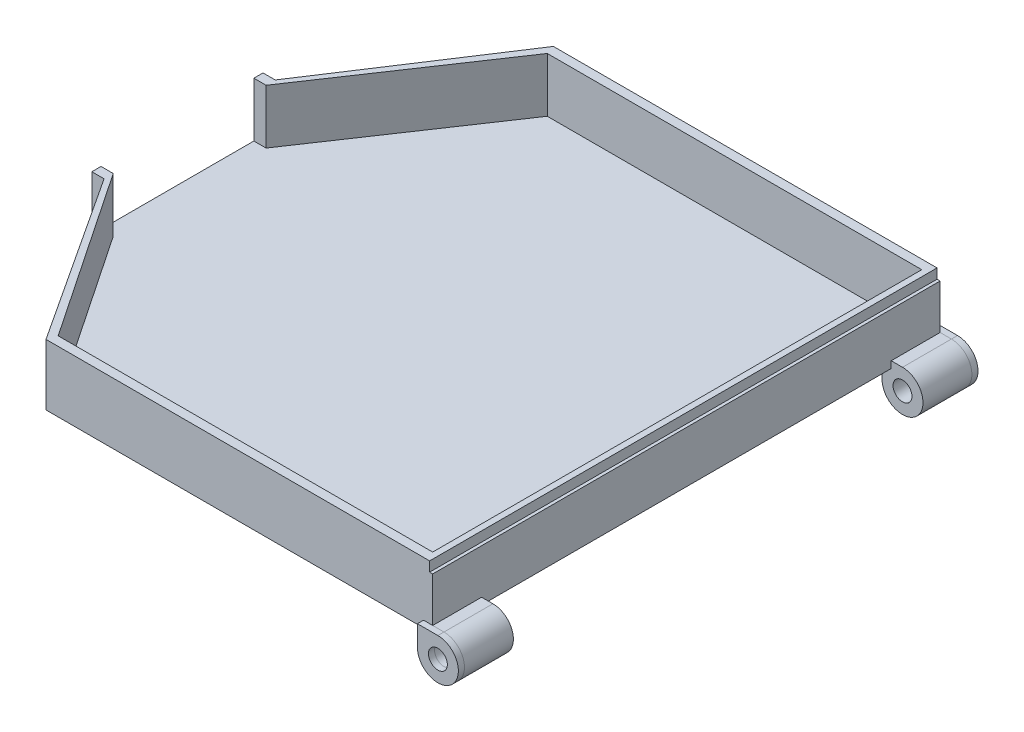
SolidWorks part; units mm, degrees
ref_plane "Спереди" through (0, 0, 0) normal (0, 0, 1) x (1, 0, 0)
ref_plane "Сверху" through (0, 0, 0) normal (0, 1, 0) x (1, 0, 0)
ref_plane "Справа" through (0, 0, 0) normal (1, 0, 0) x (0, 0, -1)
sketch "Эскиз2" plane through (0, 0, 0) normal (0, 0, 1) x (1, 0, 0)
  line L1 (28.097, -1.1018) -> (-25.7907, -1.1018)
  line L2 (28.097, 8.8982) -> (28.097, -0.0018)
  line L3 (28.097, -0.0018) -> (-29.6554, -0.0018)
  line L4 (29.597, 7.2982) -> (29.597, -0.0018)
  line L5 (-25.7907, -1.1018) -> (-31.6554, -1.1018)
  line L6 (29.597, -1.1018) -> (28.097, -1.1018)
  line L7 (28.097, -1.1018) -> (28.097, -1.5018)
  line L8 (29.097, 8.8982) -> (28.097, 8.8982)
  line L9 (-31.6554, -1.1018) -> (-51.6554, -1.1018)
  line L10 (-29.6554, -0.0018) -> (-31.6554, -0.0018)
  line L11 (29.097, 7.2982) -> (29.597, 7.2982)
  line L12 (29.097, 7.2982) -> (29.097, 8.8982)
  line L14 (-31.6554, -0.0018) -> (-51.6554, -0.0018)
  line L15 (-51.6554, -1.1018) -> (-51.6554, -0.0018)
  line L22 (31.447, -0.0018) -> (29.597, -0.0018)
  line L23 (28.097, -3.3518) -> (28.097, -1.1018)
  circle A0 centre (31.447, -3.3518) radius 1.55
  arc A1 (28.097, -3.3518) -> (31.447, -0.0018) centre (31.447, -3.3518) ccw
  point P0 (29.597, -1.1018)
  point P1 (28.097, 8.8982)
  point P4 (28.097, -0.0018)
  point P13 (12.7026, -1.1491)
  point P17 (29.097, 8.8982)
  point P18 (-36.1615, 39.8528)
  point P19 (31.447, -3.3518)
  point P21 (29.097, 7.2982)
  point P24 (31.647, -1.3675)
  point P25 (30.097, -2.9175)
  point P26 (28.097, -1.5018)
  point P27 (29.597, -1.5018)
  point P32 (34.797, -3.3518)
  point P33 (31.447, -6.7018)
  point P34 (34.797, -6.7018)
  dimension "D7" = 1.85
  dimension "D4" = 2
  dimension "D5" = 1.1
  dimension "D6" = 20
  dimension "D9" = 1.5
  dimension "D10" = 1.6
  dimension "D16" = 3.35
extrude "Бобышка-Вытянуть1" add sketch "Эскиз2" along normal blind 83
sketch "Эскиз3" plane through (0, -0.0018, 0) normal (0, 1, 0) x (1, 0, 0)
  line L0 (28.097, -83) -> (28.097, 0) construction
  line L1 (-51.6554, 0) -> (28.097, 0)
  line L2 (-51.6554, 0) -> (-51.6554, -1.5)
  line L3 (-51.6554, -1.5) -> (28.097, -1.5)
  line L4 (28.097, 0) -> (28.097, -1.5)
  line L5 (28.097, -83) -> (28.097, 0) construction
  line L6 (-51.6554, -83) -> (28.097, -83)
  line L7 (-51.6554, -83) -> (-51.6554, -81.5)
  line L8 (-51.6554, -81.5) -> (28.097, -81.5)
  line L9 (28.097, -83) -> (28.097, -81.5)
  dimension "D1" = 1.5
  dimension "D2" = 1.5
extrude "Бобышка-Вытянуть2" add sketch "Эскиз3" along normal blind 8.9 separate body
sketch "Эскиз5" plane through (0, -0.0018, 0) normal (0, 1, 0) x (1, 0, 0)
  line L0 (-31.6554, 0) -> (-31.6554, -83) construction
  line L1 (28.097, 0) -> (-51.6554, 0) construction
  line L2 (-51.6554, -83) -> (28.097, -83) construction
  line L3 (-51.6554, -83) -> (-51.6554, 0) construction
  line L4 (-51.6554, -41.5) -> (-31.6554, -41.5) construction
  line L5 (-51.6554, -27.5) -> (-33.6554, 0)
  line L6 (-33.6554, 0) -> (-31.6554, 0)
  line L8 (-32.1554, 0) -> (-51.6554, -29)
  line L9 (-51.6554, -29) -> (-51.6554, -27.5)
  line L10 (-33.6554, -83) -> (-32.1554, -83)
  line L11 (-51.6554, -54) -> (-51.6554, -55.5)
  line L12 (-51.6554, -55.5) -> (-33.6554, -83)
  line L13 (-32.1554, -83) -> (-51.6554, -54)
  point P8 (-51.6554, -41.5)
  point P11 (-51.6554, -29)
  point P12 (-51.6554, -27.5)
  point P13 (-33.6554, 0)
  point P16 (-32.1554, 0)
  line M3 (-51.6554, 0) -> (-51.6554, -83)
  line M4 (-51.6554, -83) -> (28.097, -83)
  dimension "D1" = 20
  dimension "D2" = 12.5
  dimension "D3" = 1.5
  dimension "D4" = 2
  dimension "D5" = 1.5
extrude "Бобышка-Вытянуть3" add sketch "Эскиз5" along normal blind 8.9 contours L13 L12 M4 M3 | L8 L6 L5 M3
sketch "Эскиз7" plane through (0, -0.0018, 0) normal (0, 1, 0) x (1, 0, 0)
  line L0 (-51.6554, -27.5) -> (-51.6554, 0)
  line L1 (-51.6554, -27.5) -> (-34.6372, -1.5)
  line L2 (-34.6372, -1.5) -> (-33.6554, 0)
  line L3 (29.097, 0) -> (-51.6554, 0) construction
  line L4 (-33.6554, 0) -> (-51.6554, 0)
  line L5 (-51.6554, -41.5) -> (-34.6372, -41.5) construction
  line L6 (-51.6554, -54) -> (-51.6554, -29) construction
  line L7 (-51.6554, -55.5) -> (-34.6372, -81.5)
  line L8 (-34.6372, -81.5) -> (-33.6554, -83)
  line L9 (-33.6554, -83) -> (-51.6554, -83)
  line L10 (-51.6554, -55.5) -> (-51.6554, -83)
extrude "Вырез-Вытянуть2" cut sketch "Эскиз7" against normal blind 1.5 and the other way blind 9
sketch "Эскиз11" plane through (0, 0, 83) normal (0, 0, 1) x (1, 0, 0)
  line L0 (31.447, -0.0018) -> (29.597, -0.0018)
  line L1 (28.097, -1.1018) -> (28.097, -3.3518)
  line L2 (28.097, -1.1018) -> (29.597, -1.1018)
  line L3 (29.597, -0.0018) -> (29.597, -1.1018)
  arc A0 (28.097, -3.3518) -> (31.447, -0.0018) centre (31.447, -3.3518) ccw
  circle A1 centre (31.447, -3.3518) radius 1.55
  point P0 (31.447, -3.3518)
sketch "Эскиз15" plane through (0, 0, 0) normal (0, 0, 1) x (1, 0, 0)
  line L0 (31.447, -0.0018) -> (29.597, -0.0018)
  line L1 (28.097, -1.1018) -> (28.097, -3.3518)
  line L2 (28.097, -1.1018) -> (29.597, -1.1018)
  line L3 (29.597, -0.0018) -> (29.597, -1.1018)
  arc A0 (28.097, -3.3518) -> (31.447, -0.0018) centre (31.447, -3.3518) ccw
  circle A1 centre (31.447, -3.3518) radius 1.55
  point P0 (31.447, -3.3518)
sketch "Эскиз16" plane through (0, 0, 0) normal (0, 0, 1) x (1, 0, 0)
  line L0 (31.447, -0.0018) -> (29.597, -0.0018)
  line L1 (28.097, -1.1018) -> (28.097, -3.3518)
  line L2 (28.097, -1.1018) -> (29.597, -1.1018)
  line L3 (29.597, -0.0018) -> (29.597, -1.1018)
  arc A0 (28.097, -3.3518) -> (31.447, -0.0018) centre (31.447, -3.3518) ccw
  circle A1 centre (31.447, -3.3518) radius 1.55
  point P0 (31.447, -3.3518)
extrude "Вырез-Вытянуть6" cut sketch "Эскиз15" along normal blind 75
extrude "Бобышка-Вытянуть5" add sketch "Эскиз16" along normal blind 8
sketch "Эскиз17" plane through (-51.6554, 0, 0) normal (-1, 0, 0) x (0, 0, 1)
  line L0 (54, 8.8982) -> (55.5, 8.8982)
  line L1 (27.5, -1.1018) -> (55.5, -1.1018)
  line L2 (27.5, -1.1018) -> (27.5, 8.8982)
  line L3 (27.5, 8.8982) -> (29, 8.8982)
  line L4 (55.5, -1.1018) -> (55.5, 8.8982)
  line L5 (54, -0.0018) -> (29, -0.0018)
  line L6 (54, -0.0018) -> (54, 8.8982)
  line L8 (29, -0.0018) -> (29, 8.8982)
extrude "Бобышка-Вытянуть6" add sketch "Эскиз17" along normal blind 2
sketch "Эскиз18" plane through (0, 0, 83) normal (0, 0, 1) x (1, 0, 0)
  line L3 (31.447, -0.0018) -> (28.097, -0.0018)
  line L4 (28.097, -3.3518) -> (28.097, -0.0018)
  arc A0 (28.097, -3.3518) -> (31.447, -0.0018) centre (31.447, -3.3518) ccw
  circle A1 centre (31.447, -3.3518) radius 1.55
extrude "Бобышка-Вытянуть8" add sketch "Эскиз18" along normal blind 1 separate body
sketch "Эскиз19" plane through (0, 0, 0) normal (0, 0, -1) x (-1, 0, 0)
  line L3 (-31.447, -0.0018) -> (-28.097, -0.0018)
  line L4 (-28.097, -3.3518) -> (-28.097, -0.0018)
  circle A0 centre (-31.447, -3.3518) radius 1.55
  arc A1 (-31.447, -0.0018) -> (-28.097, -3.3518) centre (-31.447, -3.3518) ccw
extrude "Бобышка-Вытянуть9" add sketch "Эскиз19" along normal blind 1 separate body
